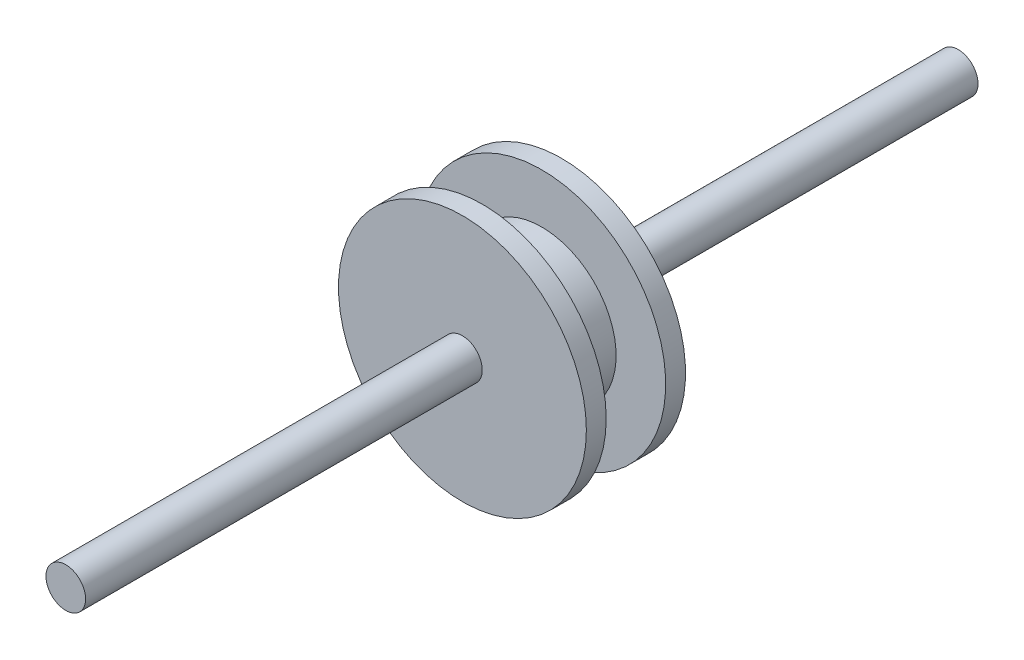
SolidWorks part; units mm, degrees
ref_plane "Front Plane" through (0, 0, 0) normal (0, 0, 1) x (1, 0, 0)
ref_plane "Top Plane" through (0, 0, 0) normal (0, 1, 0) x (1, 0, 0)
ref_plane "Right Plane" through (0, 0, 0) normal (1, 0, 0) x (0, 0, -1)
sketch "Sketch1" plane through (0, 0, 0) normal (0, 0, 1) x (1, 0, 0)
  circle A0 centre (0, 0) radius 7.5
  dimension "D1" = 15
extrude "Boss-Extrude1" add sketch "Sketch1" along normal blind 10
sketch "Sketch2" plane through (0, 0, 0) normal (0, 0, -1) x (-1, 0, 0)
  circle A0 centre (0, 0) radius 12.5
  dimension "D1" = 25
extrude "Boss-Extrude2" add sketch "Sketch2" against normal blind 2
sketch "Sketch3" plane through (0, 0, 10) normal (0, 0, 1) x (1, 0, 0)
  circle A0 centre (0, 0) radius 12.5
  dimension "D1" = 25
extrude "Boss-Extrude3" add sketch "Sketch3" against normal blind 2
sketch "Sketch4" plane through (0, 0, 10) normal (0, 0, 1) x (1, 0, 0)
  circle A0 centre (0, 0) radius 2
  dimension "D1" = 4
extrude "Boss-Extrude4" add sketch "Sketch4" along normal blind 40
sketch "Sketch5" plane through (0, 0, 0) normal (0, 0, -1) x (-1, 0, 0)
  circle A0 centre (0, 0) radius 2
  dimension "D1" = 4
extrude "Boss-Extrude5" add sketch "Sketch5" along normal blind 40
equation "\"pin_diameter_in\"=4"
equation "\"sprocket_diameter_outer\"=15"
equation "\"D1@Sketch1\"=\"sprocket_diameter_outer\""
equation "\"pin_length\"= 90"
equation "\"sprocket_length\"=10"
equation "\"D1@Boss-Extrude1\"=\"sprocket_length\""
equation "\"sprocket_edge\"=2"
equation "\"D1@Boss-Extrude2\"=\"sprocket_edge\""
equation "\"D1@Sketch3\"=\"sprocket_outer_d\""
equation "\"sprocket_outer_d\"=25"
equation "\"D1@Sketch2\"=\"sprocket_outer_d\""
equation "\"D1@Boss-Extrude3\"=\"sprocket_edge\""
equation "\"D1@Sketch4\"= \"pin_diameter_in\""
equation "\"D1@Boss-Extrude4\"=\"pin_length\"/2 - \"sprocket_length\"/2"
equation "\"D1@Sketch5\"= \"pin_diameter_in\""
equation "\"D1@Boss-Extrude5\"= \"pin_length\"/2 - \"sprocket_length\"/2"
